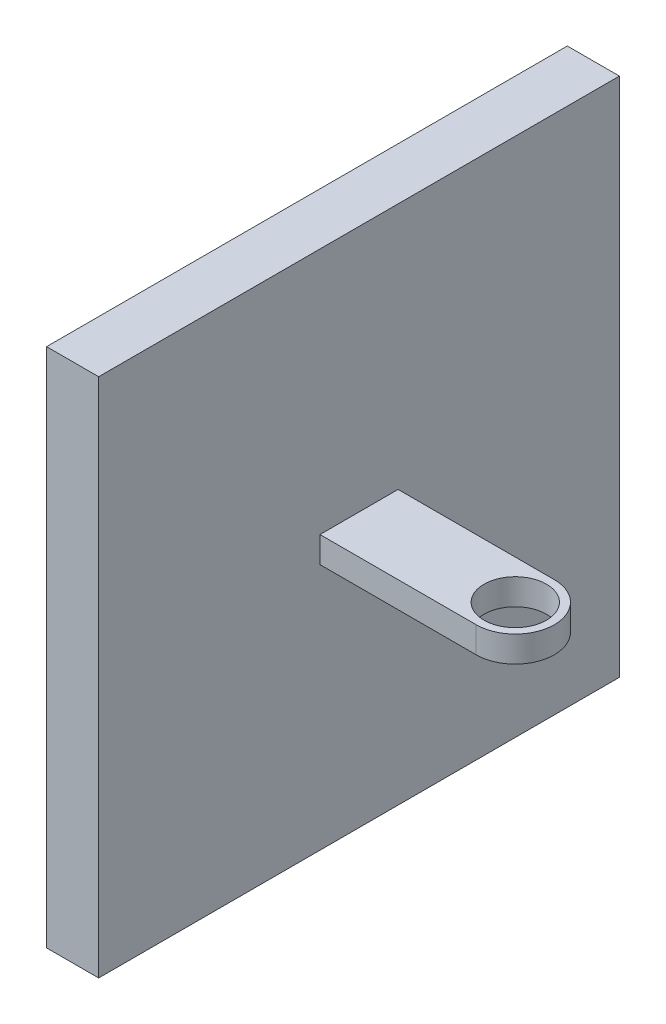
SolidWorks part; units mm, degrees
material "1.4000 (X6Cr13)"
ref_plane "前视基准面" through (0, 0, 0) normal (0, 0, 1) x (1, 0, 0)
ref_plane "上视基准面" through (0, 0, 0) normal (0, 1, 0) x (1, 0, 0)
ref_plane "右视基准面" through (0, 0, 0) normal (1, 0, 0) x (0, 0, -1)
sketch "草图1" plane through (0, 0, 0) normal (1, 0, 0) x (0, 0, -1)
  line L1 (0, 0) -> (10, 0)
  line L2 (0, 0) -> (0, 10)
  line L3 (0, 10) -> (10, 10)
  line L4 (10, 0) -> (10, 10)
extrude "凸台-拉伸1" add sketch "草图1" along normal blind 1
sketch "草图2" plane through (1, 0, 0) normal (1, 0, 0) x (0, 0, -1)
  line L3 (4.25, 4.75) -> (5.75, 4.75)
  line L4 (4.25, 4.75) -> (4.25, 5.25)
  line L5 (4.25, 5.25) -> (5.75, 5.25)
  line L6 (5.75, 4.75) -> (5.75, 5.25)
  line L7 (4.25, 4.75) -> (5.75, 5.25) construction
  line L8 (4.25, 5.25) -> (5.75, 4.75) construction
  point P5 (5, 5)
extrude "凸台-拉伸2" add sketch "草图2" along normal blind 8
sketch "草图3" plane through (0, 4.75, 0) normal (0, -1, 0) x (1, 0, 0)
  line L1 (9, -4.25) -> (1, -4.25) construction
  line L2 (9, -5.75) -> (1, -5.75) construction
  line L3 (4, -4.25) -> (1, -4.25)
  line L4 (1, -4.25) -> (1, -5.75)
  line L5 (1, 0) -> (1, -10) construction
  line L6 (1, -4.25) -> (1, -5.75) construction
  line L7 (1, -5.75) -> (4, -5.75)
  line L8 (4, -4.25) -> (9, -4.25)
  line L9 (9, -4.25) -> (9, -5.75)
  line L10 (9, -5.75) -> (4, -5.75)
  arc A0 (4, -4.25) -> (4, -5.75) centre (4, -5) cw
  point P7 (0, 0)
  line M6 (1, -5.75) -> (9, -5.75)
  line M7 (9, -5.75) -> (9, -4.25)
  line M8 (9, -4.25) -> (1, -4.25)
extrude "切除-拉伸2" cut sketch "草图3" against normal blind 2 contours A0 M8 M6 M7
sketch "草图4" plane through (0, 4.75, 0) normal (0, -1, 0) x (1, 0, 0)
  circle A0 centre (4, -5) radius 0.6
extrude "切除-拉伸3" cut sketch "草图4" against normal blind 2
